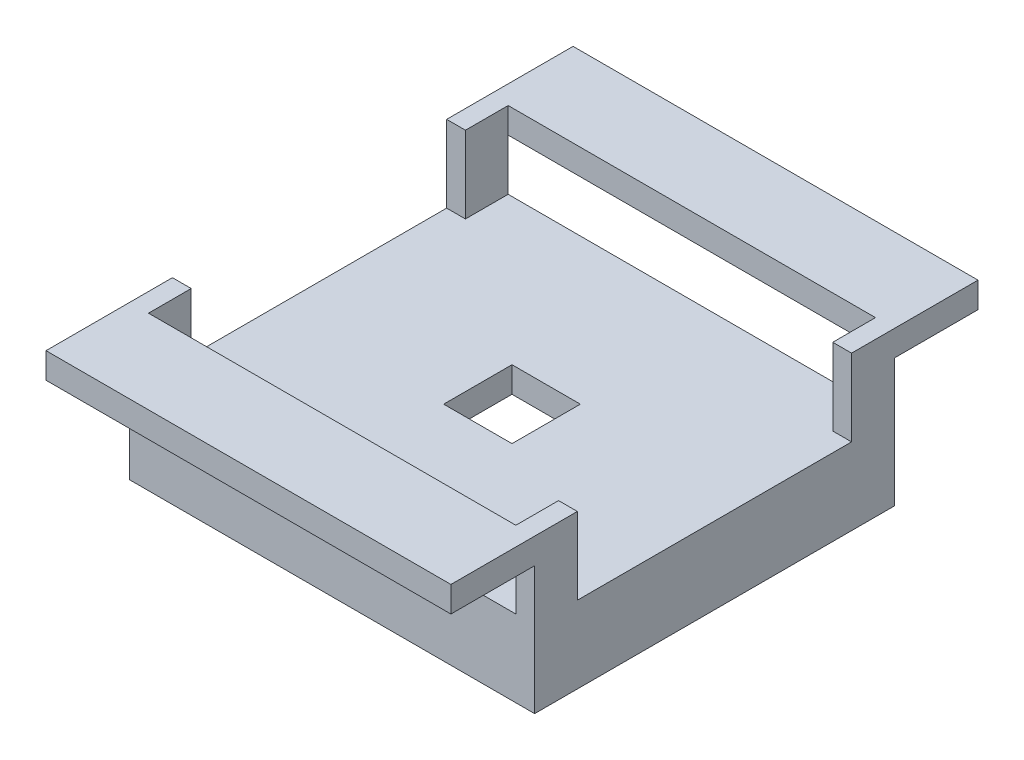
SolidWorks part; units mm, degrees
ref_plane "Front Plane" through (0, 0, 0) normal (0, 0, 1) x (1, 0, 0)
ref_plane "Top Plane" through (0, 0, 0) normal (0, 1, 0) x (1, 0, 0)
ref_plane "Right Plane" through (0, 0, 0) normal (1, 0, 0) x (0, 0, -1)
sketch "Sketch3" plane through (0, 0, 0) normal (0, 1, 0) x (1, 0, 0)
  line L1 (-23.7, -21.05) -> (23.7, -21.05)
  line L2 (-23.7, -21.05) -> (-23.7, 21.05)
  line L3 (-23.7, 21.05) -> (23.7, 21.05)
  line L4 (23.7, -21.05) -> (23.7, 21.05)
  line L5 (-23.7, -21.05) -> (23.7, 21.05) construction
  line L6 (-23.7, 21.05) -> (23.7, -21.05) construction
  point P0 (0, 0)
  dimension "D1" = 42.1
  dimension "D2" = 47.4
extrude "Boss-Extrude1" add sketch "Sketch3" along normal blind 2 and the other way blind 1
sketch "Sketch4" plane through (0, 2, 0) normal (0, 1, 0) x (1, 0, 0)
  line L1 (-23.7, 21.05) -> (-21.5, 21.05)
  line L2 (-23.7, 21.05) -> (-23.7, 16.05)
  line L3 (-23.7, 16.05) -> (-21.5, 16.05)
  line L4 (-21.5, 21.05) -> (-21.5, 16.05)
  dimension "D1" = 2.2
  dimension "D2" = 5
extrude "Boss-Extrude2" add sketch "Sketch4" along normal blind 9
sketch "Sketch6" plane through (0, 0, -21.05) normal (0, 0, -1) x (-1, 0, 0)
  line L0 (23.7, 11) -> (23.7, -1) construction
  line L1 (21.5, 11) -> (23.7, 11)
  line L2 (21.5, 11) -> (21.5, 8)
  line L3 (21.5, 8) -> (23.7, 8)
  line L4 (23.7, 11) -> (23.7, 8)
  dimension "D1" = 2.2
  dimension "D2" = 3
extrude "Boss-Extrude3" add sketch "Sketch6" along normal blind 9.8
mirror "Mirror1" about plane through (0, 0, 0) normal (1, 0, 0) of "Boss-Extrude3", "Boss-Extrude2"
sketch "Sketch10" plane through (-21.5, 0, 0) normal (1, 0, 0) x (0, 0, -1)
  line L1 (21.05, 8) -> (30.85, 8)
  line L2 (21.05, 8) -> (21.05, 11)
  line L3 (21.05, 11) -> (30.85, 11)
  line L4 (30.85, 8) -> (30.85, 11)
extrude "Boss-Extrude5" add sketch "Sketch10" along normal up to surface (43 mm away)
mirror "Mirror3" about plane through (0, 0, 0) normal (0, 0, 1) of "Boss-Extrude5", "Mirror1", "Boss-Extrude3", "Boss-Extrude2"
sketch "Sketch7" plane through (0, -1, 0) normal (0, -1, 0) x (1, 0, 0)
  line L1 (-4, 4) -> (4, 4)
  line L2 (-4, 4) -> (-4, -4)
  line L3 (-4, -4) -> (4, -4)
  line L4 (4, 4) -> (4, -4)
  line L5 (-4, 4) -> (4, -4) construction
  line L6 (-4, -4) -> (4, 4) construction
  point P0 (0, 0)
  dimension "D1" = 8
  dimension "D2" = 8
extrude "Cut-Extrude1" cut sketch "Sketch7" against normal blind 3
sketch "Sketch12" plane through (0, -1, 0) normal (0, -1, 0) x (1, 0, 0)
  line L4 (23.7, -21.05) -> (23.7, 21.05)
  line L5 (23.7, 21.05) -> (-23.7, 21.05)
  line L6 (-23.7, 21.05) -> (-23.7, -21.05)
  line L7 (-23.7, -21.05) -> (23.7, -21.05)
  line L8 (23.7, -21.05) -> (23.7, 21.05)
  line L9 (23.7, 21.05) -> (-23.7, 21.05)
  line L10 (-23.7, 21.05) -> (-23.7, -21.05)
  line L11 (-23.7, -21.05) -> (23.7, -21.05)
  dimension "D1" = 0
extrude "Boss-Extrude6" add sketch "Sketch12" along normal blind 6
loft "Cut-Loft1" cut section face at (0, -7, 0) section face at (0, -1, 0)
